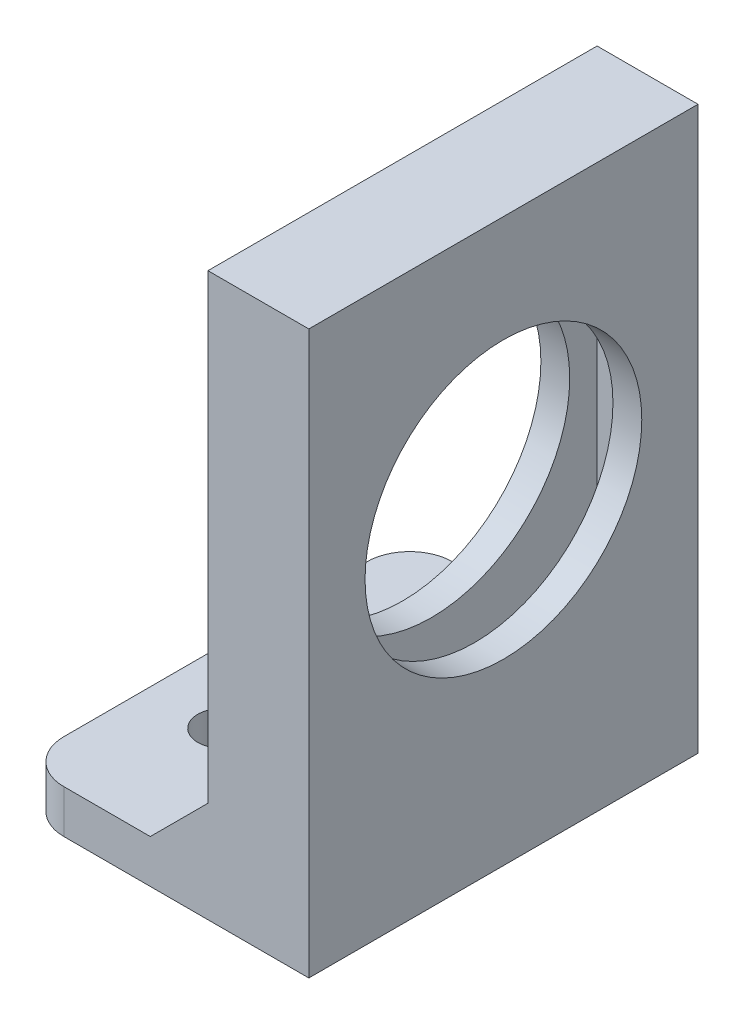
SolidWorks part; units mm, degrees
ref_plane "前视基准面" through (0, 0, 0) normal (0, 0, 1) x (1, 0, 0)
ref_plane "上视基准面" through (0, 0, 0) normal (0, 1, 0) x (1, 0, 0)
ref_plane "右视基准面" through (0, 0, 0) normal (1, 0, 0) x (0, 0, -1)
sketch "草图1" plane through (0, 0, 0) normal (0, 1, 0) x (1, 0, 0)
  line L1 (0, 0) -> (20, 0)
  line L2 (0, 0) -> (0, -27)
  line L3 (0, -27) -> (20, -27)
  line L4 (20, 0) -> (20, -27)
extrude "凸台-拉伸1" add sketch "草图1" along normal blind 3
sketch "草图2" plane through (0, 3, 0) normal (0, 1, 0) x (1, 0, 0)
  line L0 (0, -27) -> (20, -27) construction
  line L1 (20, 0) -> (18, 0)
  line L2 (20, 0) -> (20, -27)
  line L3 (20, -27) -> (18, -27)
  line L4 (18, 0) -> (18, -27)
  dimension "D1" = 2
extrude "凸台-拉伸2" add sketch "草图2" along normal blind 34
sketch "草图3" plane through (0, 3, 0) normal (0, 1, 0) x (1, 0, 0)
  line L0 (18, 0) -> (0, 0) construction
  line L1 (15, 0) -> (13, 0)
  line L2 (15, 0) -> (15, -27)
  line L3 (15, -27) -> (13, -27)
  line L4 (13, 0) -> (13, -27)
  line L5 (0, -27) -> (18, -27) construction
  dimension "D1" = 3
  dimension "D2" = 2
extrude "凸台-拉伸3" add sketch "草图3" along normal blind 34
sketch "草图4" plane through (0, 3, 0) normal (0, 1, 0) x (1, 0, 0)
  line L0 (18, 0) -> (18, -27) construction
  line L1 (15, 0) -> (18, 0)
  line L2 (15, 0) -> (15, -2)
  line L3 (15, -2) -> (18, -2)
  line L4 (18, 0) -> (18, -2)
  line L5 (15, -27) -> (15, 0) construction
  line L6 (15, -27) -> (18, -27)
  line L7 (15, -27) -> (15, -25)
  line L8 (15, -25) -> (18, -25)
  line L9 (18, -27) -> (18, -25)
  line L10 (15, -27) -> (15, 0) construction
extrude "凸台-拉伸4" add sketch "草图4" along normal blind 34
sketch "草图6" plane through (0, 37, 0) normal (0, 1, 0) x (1, 0, 0)
  line L1 (13, 0) -> (20, 0)
  line L2 (13, 0) -> (13, -27)
  line L3 (13, -27) -> (20, -27)
  line L4 (20, 0) -> (20, -27)
extrude "凸台-拉伸5" add sketch "草图6" along normal blind 2
sketch "草图7" plane through (0, 3, 0) normal (0, 1, 0) x (1, 0, 0)
  line L0 (0, 0) -> (0, -27) construction
  line L1 (13, 0) -> (0, 0) construction
  line L2 (0, -27) -> (13, -27) construction
  circle A0 centre (5, -9) radius 1.7
  circle A1 centre (5, -18) radius 1.7
  dimension "D1" = 5
  dimension "D5" = 3.4
  dimension "D6" = 3.4
  dimension "D2" = 5
  dimension "D3" = 9
  dimension "D4" = 9
extrude "切除-拉伸1" cut sketch "草图7" against normal through all
sketch "草图8" plane through (20, 0, 0) normal (1, 0, 0) x (0, 0, -1)
  line L0 (-27, 0) -> (0, 0) construction
  line L1 (0, 39) -> (0, 0) construction
  circle A0 centre (-13.5, 22) radius 9.6
  dimension "D1" = 22
  dimension "D2" = 13.5
extrude "切除-拉伸2" cut sketch "草图8" against normal blind 50
chamfer "倒角1" distance 4 angle 45 1 edges at (13, 3, 13.5)
fillet "圆角1" radius 3 2 edges at (0, 1.5, 0) (0, 1.5, 27)
